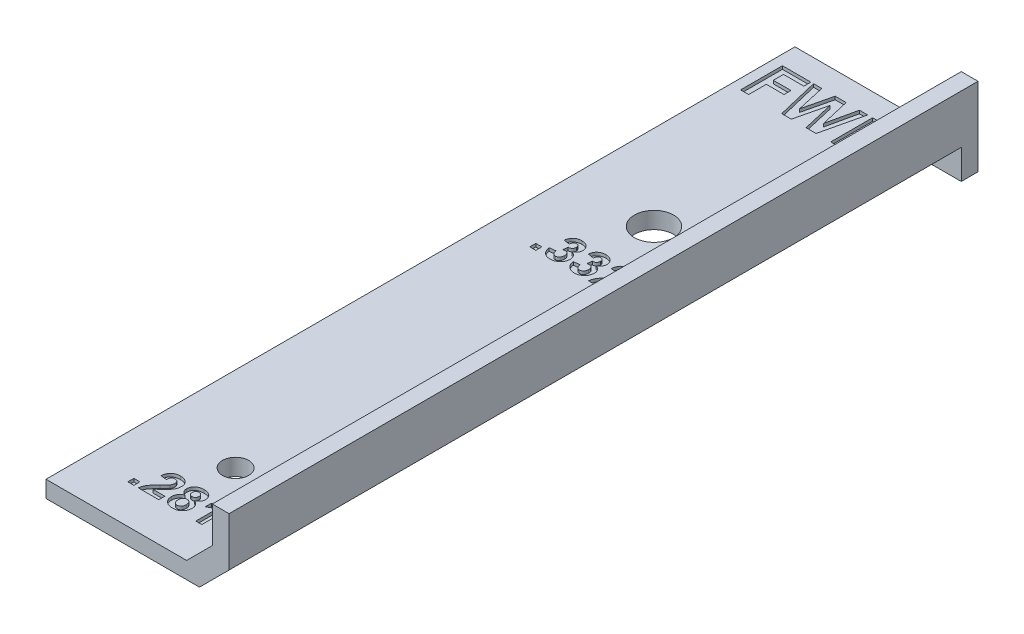
SolidWorks part; units mm, degrees
material "ABS"
ref_plane "Front Plane" through (0, 0, 0) normal (0, 0, 1) x (1, 0, 0)
ref_plane "Top Plane" through (0, 0, 0) normal (0, 1, 0) x (1, 0, 0)
ref_plane "Right Plane" through (0, 0, 0) normal (1, 0, 0) x (0, 0, -1)
sketch "Sketch1" plane through (0, 0, 0) normal (0, 0, 1) x (1, 0, 0)
  line L0 (0, 3.5921) -> (-3.5921, 0)
  line L1 (-3.5921, 0) -> (-22.225, 0)
  line L2 (-22.225, 0) -> (-22.225, 2.032)
  line L3 (-22.225, 2.032) -> (-5.1522, 2.032)
  line L4 (-5.1522, 2.032) -> (-2.032, 5.1522)
  line L5 (-2.032, 5.1522) -> (-2.032, 9.525)
  line L6 (-2.032, 9.525) -> (0, 9.525)
  line L7 (0, 9.525) -> (0, 3.5921)
  point P8 (-0.5581, 3.5921)
  dimension "D1" = 2.032
  dimension "D2" = 22.225
  dimension "D3" = 9.525
  dimension "D4" = 45
  dimension "D5" = 5.08
  dimension "D6" = 2.54
extrude "Boss-Extrude1" add sketch "Sketch1" along normal blind 88.9
hole_wizard "1/8 (0.1250) Dowel Hole2" positions "Sketch4" profile "Sketch5" hole size "1/8" standard "ANSI Inch" end condition through all
sketch "Sketch4" plane through (0, 2.032, 0) normal (0, 1, 0) x (1, 0, 0)
  line L1 (0, -88.9) -> (0, 0) construction
  line L2 (-5.1522, 0) -> (-22.225, 0) construction
  point P0 (-11.9062, -76.2)
  dimension "D1" = 76.2
  dimension "D3" = 11.9062
sketch "Sketch5" plane through (-11.9062, 2.032, 76.2) normal (1, 0, 0) x (0, 0, 1)
  line L0 (0, 0) -> (0, 2.032)
  line L1 (0, 2.032) -> (1.5875, 2.032)
  line L2 (1.5875, 2.032) -> (1.5875, 0)
  line L5 (1.5875, 0) -> (0, 0)
  line L11 (0, -6.35) -> (0, 107.95) construction
  dimension "Thru Hole Dia." = 3.175
  dimension "Thru Hole Depth" = 2.032
hole_wizard "3/16 (0.1875) Dowel Hole1" positions "Sketch8" profile "Sketch9" hole size "3/16" standard "ANSI Inch" end condition through all
sketch "Sketch8" plane through (0, 2.032, 0) normal (0, 1, 0) x (1, 0, 0)
  line L0 (-5.1522, 0) -> (-22.225, 0) construction
  line L1 (0, -88.9) -> (0, 0) construction
  point P0 (-11.9062, -25.4)
  point P5 (0, 0)
  dimension "D1" = 25.4
  dimension "D2" = 11.9062
sketch "Sketch9" plane through (-11.9062, 2.032, 25.4) normal (1, 0, 0) x (0, 0, 1)
  line L0 (0, 0) -> (0, 2.032)
  line L1 (0, 2.032) -> (2.3812, 2.032)
  line L2 (2.3812, 2.032) -> (2.3812, 0)
  line L5 (2.3812, 0) -> (0, 0)
  line L11 (0, -6.35) -> (0, 107.95) construction
  dimension "Thru Hole Dia." = 4.7625
  dimension "Thru Hole Depth" = 2.032
sketch "Sketch6" plane through (0, 0, 88.9) normal (0, 0, 1) x (1, 0, 0)
  line L0 (-22.225, 0) -> (0, 0)
  line L1 (-22.225, 2.032) -> (-22.225, 0)
  line L2 (-22.225, 2.032) -> (-5.1522, 2.032)
  line L3 (0, 9.525) -> (0, 0)
  line L4 (-5.1522, 2.032) -> (-2.032, 5.1522)
  line L5 (-2.032, 5.1522) -> (-2.032, 9.525)
  line L6 (0, 9.525) -> (-2.032, 9.525) construction
  line L7 (-2.032, 9.525) -> (0, 9.525)
extrude "Boss-Extrude2" add sketch "Sketch6" against normal blind 2.032 from surface at -88.9 starting at face at (-7.1573, 3.9823, 0)
sketch "Sketch10" plane through (0, 2.032, 0) normal (0, 1, 0) x (1, 0, 0)
  text T0 "FWD" font "Arial" height 5.08
  text T1 ".332" font "Arial" height 3.81
  text T2 ".281" font "Arial" height 3.81
extrude "Cut-Extrude2" cut sketch "Sketch10" against normal blind 0.381
